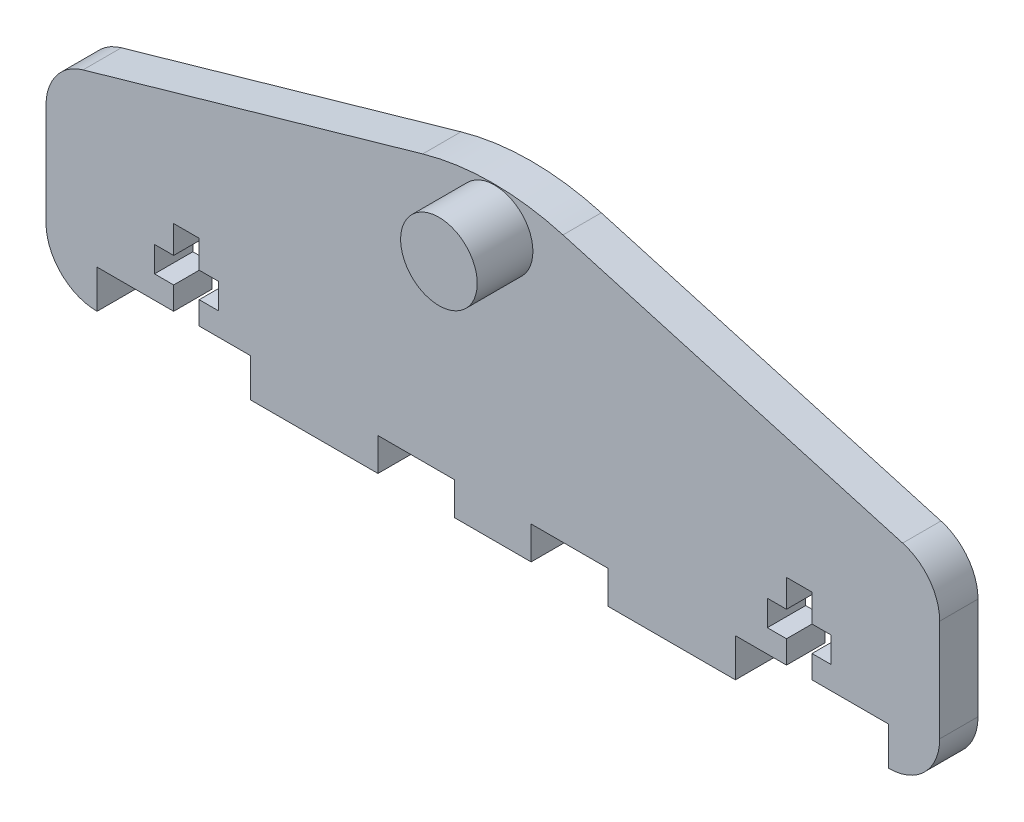
SolidWorks part; units mm, degrees
ref_plane "Plan de face" through (0, 0, 0) normal (0, 0, 1) x (1, 0, 0)
ref_plane "Plan de dessus" through (0, 0, 0) normal (0, 1, 0) x (1, 0, 0)
ref_plane "Plan de droite" through (0, 0, 0) normal (1, 0, 0) x (0, 0, -1)
sketch "Esquisse1" plane through (0, 0, 0) normal (0, 0, 1) x (1, 0, 0)
  line L0 (-160.4944, 41.6445) -> (-27.4721, 79.6508)
  line L1 (-155, -37.5) -> (155, -37.5)
  line L2 (-175, -17.5) -> (-175, 22.414)
  line L3 (-175, 37.5) -> (175, 37.5) construction
  line L4 (175, -17.5) -> (175, 22.414)
  line L5 (-175, -37.5) -> (175, 37.5) construction
  line L6 (-175, 37.5) -> (175, -37.5) construction
  line L7 (27.4721, 79.6508) -> (160.4944, 41.6445)
  line L8 (0, 83.4984) -> (0, -16.5016) construction
  line L9 (-175, -17.5) -> (175, -17.5) construction
  line L10 (-175, 22.414) -> (175, 22.414) construction
  arc A0 (27.4721, 79.6508) -> (-27.4721, 79.6508) centre (0, -16.5016) ccw
  circle A1 centre (0, 68.1651) radius 5
  arc A2 (175, 22.414) -> (160.4944, 41.6445) centre (155, 22.414) ccw
  arc A3 (155, -37.5) -> (175, -17.5) centre (155, -17.5) ccw
  arc A4 (-155, -37.5) -> (-175, -17.5) centre (-155, -17.5) cw
  arc A5 (-175, 22.414) -> (-160.4944, 41.6445) centre (-155, 22.414) cw
  point P0 (0, 0)
  dimension "D3" = 100
  dimension "D4" = 10
  dimension "D5" = 20
  dimension "D1" = 350
  dimension "D2" = 75
  dimension "D6" = 15.3333
extrude "Boss.-Extru.1" add sketch "Esquisse1" along normal blind 15
sketch "Esquisse2" plane through (0, 0, 15) normal (0, 0, 1) x (1, 0, 0)
  line L0 (-175, -17.5) -> (175, -17.5) construction
  line L1 (175, -17.5) -> (175, 22.414) construction
  line L2 (115, -60) -> (125, -60)
  line L3 (115, -60) -> (115, -37.5)
  line L4 (115, 7.276) -> (125, 7.276)
  line L5 (125, -60) -> (125, -37.5)
  line L6 (115, -60) -> (125, 7.276) construction
  line L7 (115, 7.276) -> (125, -60) construction
  line L8 (0, 0) -> (0, -37.5) construction
  line L9 (-155, -37.5) -> (155, -37.5) construction
  line L10 (120, 7.276) -> (120, -60) construction
  line L11 (107.5, -13.5497) -> (115, -13.5497)
  line L12 (107.5, -13.5497) -> (107.5, -3.5497)
  line L13 (107.5, -3.5497) -> (115, -3.5497)
  line L14 (132.5, -13.5497) -> (132.5, -3.5497)
  line L15 (107.5, -13.5497) -> (132.5, -3.5497) construction
  line L16 (107.5, -3.5497) -> (132.5, -13.5497) construction
  line L17 (135, -22.5) -> (135, -37.5)
  line L18 (135, -22.5) -> (125, -22.5)
  line L19 (135, -37.5) -> (125, -37.5)
  line L20 (95, -22.5) -> (95, -37.5)
  line L21 (95, -22.5) -> (95, -37.5)
  line L22 (-115, -60) -> (-125, -60)
  line L23 (-125, -60) -> (-125, -37.5)
  line L24 (45, -24.6183) -> (45, -37.5)
  line L25 (45, -24.6183) -> (45, -37.5)
  line L26 (45, -24.6183) -> (15, -24.6183)
  line L27 (45, -37.5) -> (15, -37.5)
  line L28 (15, -24.6183) -> (15, -37.5)
  line L29 (-115, 7.276) -> (-125, 7.276)
  line L30 (-107.5, -13.5497) -> (-107.5, -3.5497)
  line L31 (-132.5, -13.5497) -> (-132.5, -3.5497)
  line L32 (-107.5, -3.5497) -> (-115, -3.5497)
  line L33 (-107.5, -13.5497) -> (-115, -13.5497)
  line L34 (-115, -60) -> (-115, -37.5)
  line L35 (-135, -37.5) -> (-125, -37.5)
  line L36 (-135, -22.5) -> (-125, -22.5)
  line L37 (-95, -22.5) -> (-95, -37.5)
  line L38 (-45, -24.6183) -> (-45, -37.5)
  line L39 (-45, -37.5) -> (-15, -37.5)
  line L40 (-15, -24.6183) -> (-15, -37.5)
  line L41 (-45, -24.6183) -> (-15, -24.6183)
  line L42 (-135, -22.5) -> (-135, -37.5)
  line L46 (45, -37.5) -> (45, -22.5) construction
  line L47 (95, -37.5) -> (95, -22.5) construction
  line L48 (-155, -37.5) -> (155, -37.5) construction
  line L49 (115, -22.5) -> (115, -13.5497)
  line L50 (125, -22.5) -> (125, -13.5497)
  line L51 (115, -22.5) -> (95, -22.5)
  line L52 (115, -3.5497) -> (115, 7.276)
  line L53 (125, -3.5497) -> (132.5, -3.5497)
  line L54 (125, -3.5497) -> (125, 7.276)
  line L55 (125, -13.5497) -> (132.5, -13.5497)
  line L56 (-125, -22.5) -> (-125, -13.5497)
  line L57 (115, -37.5) -> (95, -37.5)
  line L58 (-115, -22.5) -> (-115, -13.5497)
  line L59 (-115, -22.5) -> (-95, -22.5)
  line L60 (-125, -13.5497) -> (-132.5, -13.5497)
  line L61 (-125, -3.5497) -> (-125, 7.276)
  line L62 (-115, -3.5497) -> (-115, 7.276)
  line L63 (-125, -3.5497) -> (-132.5, -3.5497)
  line L64 (-115, -37.5) -> (-95, -37.5)
  point P4 (120, -26.362)
  point P16 (120, -8.5497)
  line M24 (-155, -37.5) -> (155, -37.5)
  dimension "D1" = 50
  dimension "D2" = 10
  dimension "D3" = 25
  dimension "D4" = 10
  dimension "D5" = 15
  dimension "D6" = 40
  dimension "D8" = 30
extrude "Enlèv. mat.-Extru.1" cut sketch "Esquisse2" against normal blind 15 contours L50 L55 L14 L53 L54 L4 L52 L13 L12 L11 L49 L51 L20 L17 L18 M24 | L26 L28 L24 M24 | L41 L38 L40 M24 | L61 L63 L31 L60 L56 L36 L42 L37 L59 L58 L33 L30 L32 L62 L29 M24
sketch "Esquisse3" plane through (0, 0, 0) normal (0, 0, -1) x (-1, 0, 0)
  line L0 (135, -22.5) -> (135, -37.5)
  line L1 (135, -22.5) -> (155, -22.5)
  line L2 (135, -37.5) -> (155, -37.5)
  line L3 (155, -22.5) -> (155, -37.5)
  line L4 (155, -37.5) -> (155, -22.5) construction
  line L5 (0, -37.5) -> (0, 30.1236) construction
  line L6 (15, -37.5) -> (-15, -37.5) construction
  line L7 (-155, -22.5) -> (-155, -37.5)
  line L8 (-135, -37.5) -> (-155, -37.5)
  line L9 (-135, -22.5) -> (-135, -37.5)
  line L10 (-135, -22.5) -> (-155, -22.5)
extrude "Enlèv. mat.-Extru.2" cut sketch "Esquisse3" against normal blind 15
sketch "Esquisse5" plane through (0, 0, 15) normal (0, 0, 1) x (1, 0, 0)
  circle A0 centre (0.6859, 68.1651) radius 15
  dimension "D1" = 30
extrude "Boss.-Extru.2" add sketch "Esquisse5" along normal blind 21.8
